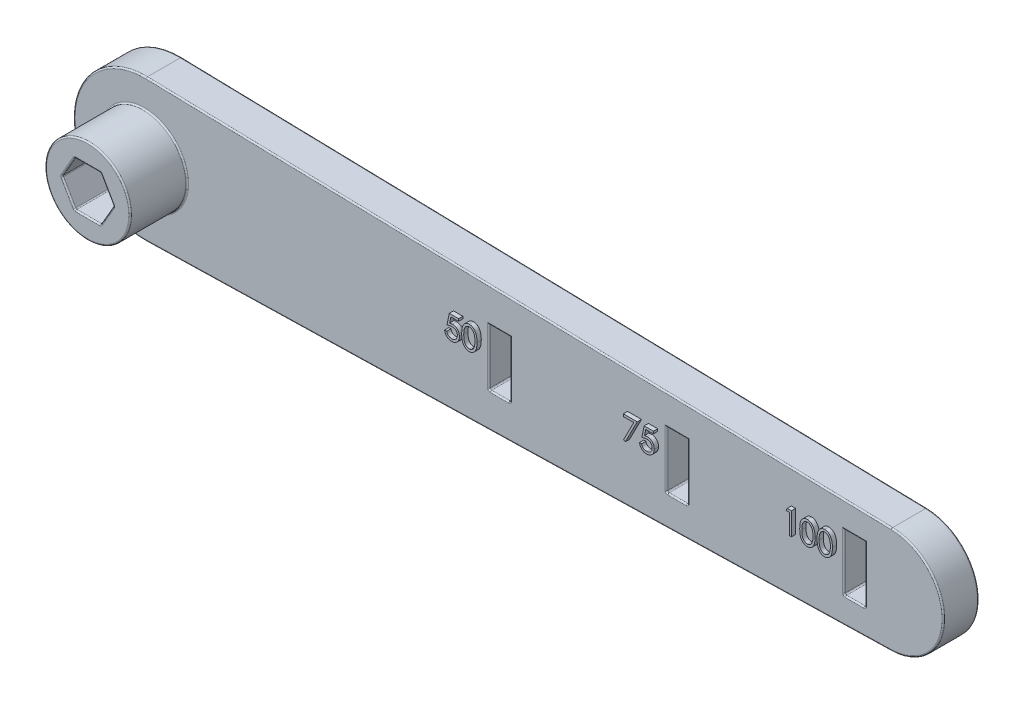
SolidWorks part; units mm, degrees
ref_plane "Front Plane" through (0, 0, 0) normal (0, 0, 1) x (1, 0, 0)
ref_plane "Top Plane" through (0, 0, 0) normal (0, 1, 0) x (1, 0, 0)
ref_plane "Right Plane" through (0, 0, 0) normal (1, 0, 0) x (0, 0, -1)
sketch "Sketch3" plane through (0, 0, 0) normal (0, 0, 1) x (1, 0, 0)
  line L0 (0.2381, 9.9972) -> (105.1786, 7.4979)
  line L1 (105.1786, -7.4979) -> (0.2381, -9.9972)
  arc A0 (0.2381, 9.9972) -> (0.2381, -9.9972) centre (0, 0) ccw
  arc A1 (105.1786, -7.4979) -> (105.1786, 7.4979) centre (105, 0) ccw
  dimension "D1" = 20
  dimension "D2" = 15
  dimension "D3" = 105
extrude "Boss-Extrude1" add sketch "Sketch3" along normal blind 5
sketch "Sketch2" plane through (0, 0, 0) normal (0, 0, 1) x (1, 0, 0)
  line L2 (3.6373, 0) -> (1.8187, 3.15)
  line L3 (1.8187, 3.15) -> (-1.8187, 3.15)
  line L4 (-1.8187, 3.15) -> (-3.6373, 0)
  line L5 (-3.6373, 0) -> (-1.8187, -3.15)
  line L6 (-1.8187, -3.15) -> (1.8187, -3.15)
  line L7 (1.8187, -3.15) -> (3.6373, 0)
  circle A1 centre (0, 0) radius 3.15 construction
  point P1 (0, 0)
  dimension "D1" = 6.3
extrude "Cut-Extrude2" cut sketch "Sketch2" along normal up to next
sketch "Sketch4" plane through (0, 0, 5) normal (0, 0, 1) x (1, 0, 0)
  line L1 (98.5, 4) -> (101.5, 4)
  line L2 (98.5, 4) -> (98.5, -4)
  line L3 (98.5, -4) -> (101.5, -4)
  line L4 (101.5, 4) -> (101.5, -4)
  line L5 (100, -4) -> (100, 4) construction
  line L6 (0, 0) -> (112.5, 0) construction
  line L7 (73.5, 4) -> (76.5, 4)
  line L8 (73.5, 4) -> (73.5, -4)
  line L9 (73.5, -4) -> (76.5, -4)
  line L10 (76.5, 4) -> (76.5, -4)
  line L11 (75, -4) -> (75, 4) construction
  line L12 (48.5, 4) -> (51.5, 4)
  line L13 (48.5, 4) -> (48.5, -4)
  line L14 (48.5, -4) -> (51.5, -4)
  line L15 (51.5, 4) -> (51.5, -4)
  line L16 (50, -4) -> (50, 4) construction
  arc A0 (105.1786, -7.4979) -> (105.1786, 7.4979) centre (105, 0) ccw construction
  point P4 (100, 0)
  point P5 (100, 4.5968)
  point P8 (100, -4.9517)
  point P27 (0, 0)
  point P28 (75, 9.6922)
  point P29 (76.5, 6.5907)
  point P30 (75, 6.5907)
  point P31 (51.5, 6.203)
  point P32 (50, 6.203)
  point P33 (50, 0)
  point P34 (75, 0)
  dimension "D1" = 8
  dimension "D3" = 3
  dimension "D4" = 50
  dimension "D5" = 75
  dimension "D6" = 100
extrude "Cut-Extrude3" cut sketch "Sketch4" against normal up to next
sketch "Sketch6" plane through (0, 0, 5) normal (0, 0, 1) x (1, 0, 0)
  line L1 (3.6373, 0) -> (1.8187, 3.15) construction
  line L2 (3.6373, 0) -> (1.8187, 3.15)
  line L3 (1.8187, 3.15) -> (-1.8187, 3.15)
  line L4 (-1.8187, 3.15) -> (-3.6373, 0)
  line L5 (-3.6373, 0) -> (-1.8187, -3.15)
  line L6 (-1.8187, -3.15) -> (1.8187, -3.15)
  line L7 (1.8187, -3.15) -> (3.6373, 0)
  circle A0 centre (0, 0) radius 6
  circle A2 centre (0, 0) radius 3.15 construction
  dimension "D1" = 12
extrude "Boss-Extrude3" add sketch "Sketch6" along normal blind 8
fillet "Fillet1" radius 0.2 58 edges at (51.5, -4, 2.5) (48.5, -4, 2.5) (101.5, -4, 2.5) (98.5, -4, 2.5) (76.5, -4, 2.5) (73.5, -4, 2.5) (76.5, 0, 0) (75, -4, 0) (73.5, 0, 0) (52.7083, 8.7475, 0) (51.5, 0, 0) (50, -4, 0) (48.5, 0, 0) (-10, 0, 0) (52.7083, -8.7475, 0) (112.5, 0, 0) (101.5, 0, 0) (100, -4, 0) (98.5, 0, 0) (100, -4, 5) (101.5, 0, 5) (52.7083, 8.7475, 5) (112.5, 0, 5) (52.7083, -8.7475, 5) (-10, 0, 5) (48.5, 0, 5) (50, -4, 5) (51.5, 0, 5) (73.5, 0, 5) (75, -4, 5) (76.5, 0, 5) (98.5, 0, 5) (6, 0, 5) (6, 0, 13) (50, 4, 0) (75, 4, 0) (100, 4, 0) (100, 4, 5) (75, 4, 5) (50, 4, 5) (0, -3.15, 0) (-2.728, -1.575, 0) (-2.728, 1.575, 0) (0, 3.15, 0) (2.728, 1.575, 0) (2.728, -1.575, 0) (2.728, 1.575, 13) (0, -3.15, 13) (-2.728, 1.575, 13) (3.6373, 0, 6.5) (2.728, -1.575, 13) (1.8187, -3.15, 6.5) (-1.8187, 3.15, 6.5) (0, 3.15, 13) (1.8187, 3.15, 6.5) (-1.8187, -3.15, 6.5) (-2.728, -1.575, 13) (-3.6373, 0, 6.5)
sketch "Sketch5" plane through (0, 0, 5) normal (0, 0, 1) x (1, 0, 0)
  line L0 (0, 0) -> (112.3, 0) construction
  line L1 (48.5, 4) -> (48.5, -3.8) construction
  line L2 (73.5, 4) -> (73.5, -3.8) construction
  line L3 (98.5, 4) -> (98.5, -3.8) construction
  arc A0 (105.1738, -7.2979) -> (105.1738, 7.2979) centre (105, 0) ccw construction
  text T0 "50"
  text T1 "75"
  text T2 "100"
  dimension "D1" = 5.8
  dimension "D2" = 5.8
  dimension "D3" = 8.2
extrude "Boss-Extrude2" add sketch "Sketch5" along normal blind 0.6
